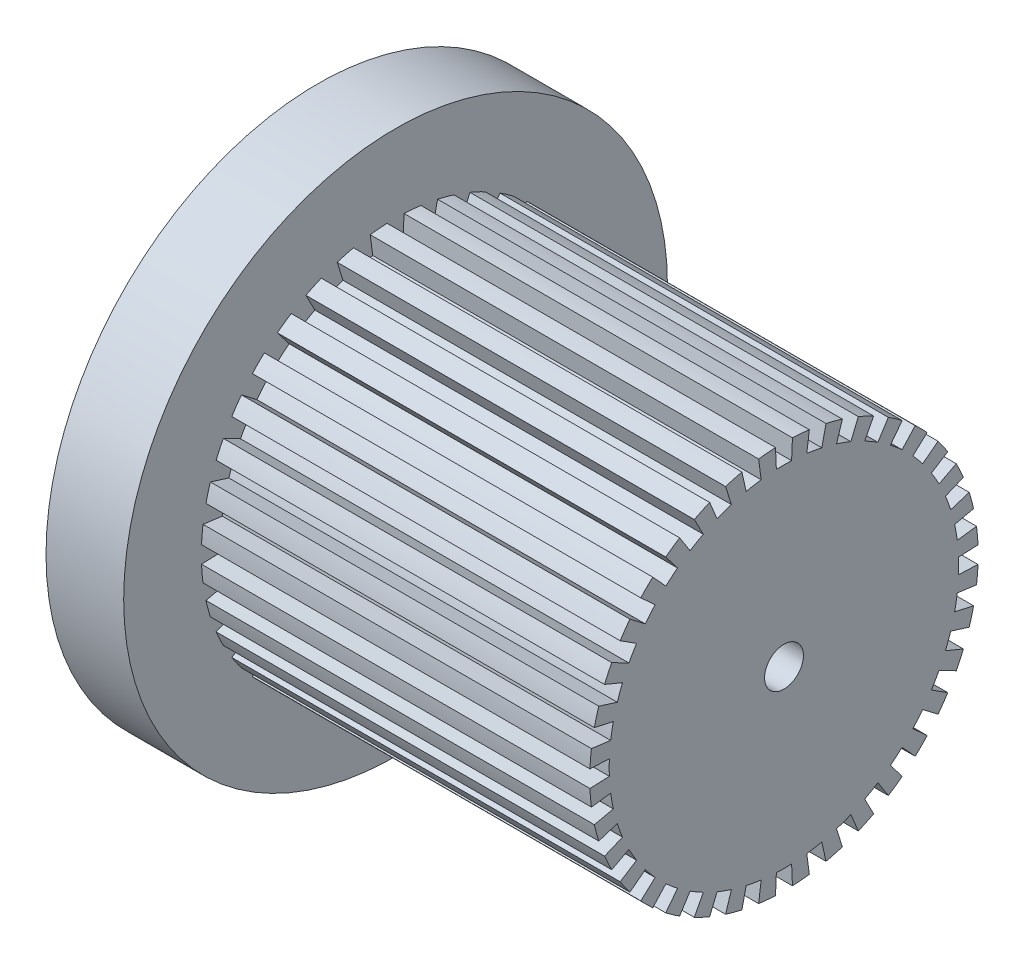
SolidWorks part; units mm, degrees
ref_plane "Front Plane" through (0, 0, 0) normal (0, 0, 1) x (1, 0, 0)
ref_plane "Top Plane" through (0, 0, 0) normal (0, 1, 0) x (1, 0, 0)
ref_plane "Right Plane" through (0, 0, 0) normal (1, 0, 0) x (0, 0, -1)
sketch "Sketch1" plane through (0, 0, 0) normal (1, 0, 0) x (0, 0, -1)
  line L0 (0, 0) -> (0, 2.2) construction
  line L1 (0.096, 2.1979) -> (0.109, 2.4976)
  line L2 (-0.096, 2.1979) -> (-0.109, 2.4976)
  line L3 (0.4762, 2.1479) -> (0.5411, 2.4407)
  line L4 (0.2872, 2.1812) -> (0.3263, 2.4786)
  line L5 (0.8419, 2.0325) -> (0.9567, 2.3097)
  line L6 (0.6616, 2.0982) -> (0.7518, 2.3843)
  line L7 (1.1821, 1.8555) -> (1.3432, 2.1085)
  line L8 (1.0158, 1.9514) -> (1.1544, 2.2175)
  line L9 (1.4863, 1.622) -> (1.689, 1.8432)
  line L10 (1.3393, 1.7454) -> (1.5219, 1.9834)
  line L11 (1.7454, 1.3393) -> (1.9834, 1.5219)
  line L12 (1.622, 1.4863) -> (1.8432, 1.689)
  line L13 (1.9514, 1.0158) -> (2.2175, 1.1544)
  line L14 (1.8555, 1.1821) -> (2.1085, 1.3432)
  line L15 (2.0982, 0.6616) -> (2.3843, 0.7518)
  line L16 (2.0325, 0.8419) -> (2.3097, 0.9567)
  line L17 (2.1812, 0.2872) -> (2.4786, 0.3263)
  line L18 (2.1479, 0.4762) -> (2.4407, 0.5411)
  line L19 (2.1979, -0.096) -> (2.4976, -0.109)
  line L20 (2.1979, 0.096) -> (2.4976, 0.109)
  line L21 (2.1479, -0.4762) -> (2.4407, -0.5411)
  line L22 (2.1812, -0.2872) -> (2.4786, -0.3263)
  line L23 (2.0325, -0.8419) -> (2.3097, -0.9567)
  line L24 (2.0982, -0.6616) -> (2.3843, -0.7518)
  line L25 (1.8555, -1.1821) -> (2.1085, -1.3432)
  line L26 (1.9514, -1.0158) -> (2.2175, -1.1544)
  line L27 (1.622, -1.4863) -> (1.8432, -1.689)
  line L28 (1.7454, -1.3393) -> (1.9834, -1.5219)
  line L29 (1.3393, -1.7454) -> (1.5219, -1.9834)
  line L30 (1.4863, -1.622) -> (1.689, -1.8432)
  line L31 (1.0158, -1.9514) -> (1.1544, -2.2175)
  line L32 (1.1821, -1.8555) -> (1.3432, -2.1085)
  line L33 (0.6616, -2.0982) -> (0.7518, -2.3843)
  line L34 (0.8419, -2.0325) -> (0.9567, -2.3097)
  line L35 (0.2872, -2.1812) -> (0.3263, -2.4786)
  line L36 (0.4762, -2.1479) -> (0.5411, -2.4407)
  line L37 (-0.096, -2.1979) -> (-0.109, -2.4976)
  line L38 (0.096, -2.1979) -> (0.109, -2.4976)
  line L39 (-0.4762, -2.1479) -> (-0.5411, -2.4407)
  line L40 (-0.2872, -2.1812) -> (-0.3263, -2.4786)
  line L41 (-0.8419, -2.0325) -> (-0.9567, -2.3097)
  line L42 (-0.6616, -2.0982) -> (-0.7518, -2.3843)
  line L43 (-1.1821, -1.8555) -> (-1.3432, -2.1085)
  line L44 (-1.0158, -1.9514) -> (-1.1544, -2.2175)
  line L45 (-1.4863, -1.622) -> (-1.689, -1.8432)
  line L46 (-1.3393, -1.7454) -> (-1.5219, -1.9834)
  line L47 (-1.7454, -1.3393) -> (-1.9834, -1.5219)
  line L48 (-1.622, -1.4863) -> (-1.8432, -1.689)
  line L49 (-1.9514, -1.0158) -> (-2.2175, -1.1544)
  line L50 (-1.8555, -1.1821) -> (-2.1085, -1.3432)
  line L51 (-2.0982, -0.6616) -> (-2.3843, -0.7518)
  line L52 (-2.0325, -0.8419) -> (-2.3097, -0.9567)
  line L53 (-2.1812, -0.2872) -> (-2.4786, -0.3263)
  line L54 (-2.1479, -0.4762) -> (-2.4407, -0.5411)
  line L55 (-2.1979, 0.096) -> (-2.4976, 0.109)
  line L56 (-2.1979, -0.096) -> (-2.4976, -0.109)
  line L57 (-2.1479, 0.4762) -> (-2.4407, 0.5411)
  line L58 (-2.1812, 0.2872) -> (-2.4786, 0.3263)
  line L59 (-2.0325, 0.8419) -> (-2.3097, 0.9567)
  line L60 (-2.0982, 0.6616) -> (-2.3843, 0.7518)
  line L61 (-1.8555, 1.1821) -> (-2.1085, 1.3432)
  line L62 (-1.9514, 1.0158) -> (-2.2175, 1.1544)
  line L63 (-1.622, 1.4863) -> (-1.8432, 1.689)
  line L64 (-1.7454, 1.3393) -> (-1.9834, 1.5219)
  line L65 (-1.3393, 1.7454) -> (-1.5219, 1.9834)
  line L66 (-1.4863, 1.622) -> (-1.689, 1.8432)
  line L67 (-1.0158, 1.9514) -> (-1.1544, 2.2175)
  line L68 (-1.1821, 1.8555) -> (-1.3432, 2.1085)
  line L69 (-0.6616, 2.0982) -> (-0.7518, 2.3843)
  line L70 (-0.8419, 2.0325) -> (-0.9567, 2.3097)
  line L71 (-0.2872, 2.1812) -> (-0.3263, 2.4786)
  line L72 (-0.4762, 2.1479) -> (-0.5411, 2.4407)
  arc A0 (0.096, 2.1979) -> (-0.096, 2.1979) centre (0, 0) ccw
  arc A1 (-0.109, 2.4976) -> (-0.3263, 2.4786) centre (0, 0) ccw
  arc A2 (0.4762, 2.1479) -> (0.2872, 2.1812) centre (0, 0) ccw
  arc A3 (0.3263, 2.4786) -> (0.109, 2.4976) centre (0, 0) ccw
  arc A4 (0.8419, 2.0325) -> (0.6616, 2.0982) centre (0, 0) ccw
  arc A5 (0.7518, 2.3843) -> (0.5411, 2.4407) centre (0, 0) ccw
  arc A6 (1.1821, 1.8555) -> (1.0158, 1.9514) centre (0, 0) ccw
  arc A7 (1.1544, 2.2175) -> (0.9567, 2.3097) centre (0, 0) ccw
  arc A8 (1.4863, 1.622) -> (1.3393, 1.7454) centre (0, 0) ccw
  arc A9 (1.5219, 1.9834) -> (1.3432, 2.1085) centre (0, 0) ccw
  arc A10 (1.7454, 1.3393) -> (1.622, 1.4863) centre (0, 0) ccw
  arc A11 (1.8432, 1.689) -> (1.689, 1.8432) centre (0, 0) ccw
  arc A12 (1.9514, 1.0158) -> (1.8555, 1.1821) centre (0, 0) ccw
  arc A13 (2.1085, 1.3432) -> (1.9834, 1.5219) centre (0, 0) ccw
  arc A14 (2.0982, 0.6616) -> (2.0325, 0.8419) centre (0, 0) ccw
  arc A15 (2.3097, 0.9567) -> (2.2175, 1.1544) centre (0, 0) ccw
  arc A16 (2.1812, 0.2872) -> (2.1479, 0.4762) centre (0, 0) ccw
  arc A17 (2.4407, 0.5411) -> (2.3843, 0.7518) centre (0, 0) ccw
  arc A18 (2.1979, -0.096) -> (2.1979, 0.096) centre (0, 0) ccw
  arc A19 (2.4976, 0.109) -> (2.4786, 0.3263) centre (0, 0) ccw
  arc A20 (2.1479, -0.4762) -> (2.1812, -0.2872) centre (0, 0) ccw
  arc A21 (2.4786, -0.3263) -> (2.4976, -0.109) centre (0, 0) ccw
  arc A22 (2.0325, -0.8419) -> (2.0982, -0.6616) centre (0, 0) ccw
  arc A23 (2.3843, -0.7518) -> (2.4407, -0.5411) centre (0, 0) ccw
  arc A24 (1.8555, -1.1821) -> (1.9514, -1.0158) centre (0, 0) ccw
  arc A25 (2.2175, -1.1544) -> (2.3097, -0.9567) centre (0, 0) ccw
  arc A26 (1.622, -1.4863) -> (1.7454, -1.3393) centre (0, 0) ccw
  arc A27 (1.9834, -1.5219) -> (2.1085, -1.3432) centre (0, 0) ccw
  arc A28 (1.3393, -1.7454) -> (1.4863, -1.622) centre (0, 0) ccw
  arc A29 (1.689, -1.8432) -> (1.8432, -1.689) centre (0, 0) ccw
  arc A30 (1.0158, -1.9514) -> (1.1821, -1.8555) centre (0, 0) ccw
  arc A31 (1.3432, -2.1085) -> (1.5219, -1.9834) centre (0, 0) ccw
  arc A32 (0.6616, -2.0982) -> (0.8419, -2.0325) centre (0, 0) ccw
  arc A33 (0.9567, -2.3097) -> (1.1544, -2.2175) centre (0, 0) ccw
  arc A34 (0.2872, -2.1812) -> (0.4762, -2.1479) centre (0, 0) ccw
  arc A35 (0.5411, -2.4407) -> (0.7518, -2.3843) centre (0, 0) ccw
  arc A36 (-0.096, -2.1979) -> (0.096, -2.1979) centre (0, 0) ccw
  arc A37 (0.109, -2.4976) -> (0.3263, -2.4786) centre (0, 0) ccw
  arc A38 (-0.4762, -2.1479) -> (-0.2872, -2.1812) centre (0, 0) ccw
  arc A39 (-0.3263, -2.4786) -> (-0.109, -2.4976) centre (0, 0) ccw
  arc A40 (-0.8419, -2.0325) -> (-0.6616, -2.0982) centre (0, 0) ccw
  arc A41 (-0.7518, -2.3843) -> (-0.5411, -2.4407) centre (0, 0) ccw
  arc A42 (-1.1821, -1.8555) -> (-1.0158, -1.9514) centre (0, 0) ccw
  arc A43 (-1.1544, -2.2175) -> (-0.9567, -2.3097) centre (0, 0) ccw
  arc A44 (-1.4863, -1.622) -> (-1.3393, -1.7454) centre (0, 0) ccw
  arc A45 (-1.5219, -1.9834) -> (-1.3432, -2.1085) centre (0, 0) ccw
  arc A46 (-1.7454, -1.3393) -> (-1.622, -1.4863) centre (0, 0) ccw
  arc A47 (-1.8432, -1.689) -> (-1.689, -1.8432) centre (0, 0) ccw
  arc A48 (-1.9514, -1.0158) -> (-1.8555, -1.1821) centre (0, 0) ccw
  arc A49 (-2.1085, -1.3432) -> (-1.9834, -1.5219) centre (0, 0) ccw
  arc A50 (-2.0982, -0.6616) -> (-2.0325, -0.8419) centre (0, 0) ccw
  arc A51 (-2.3097, -0.9567) -> (-2.2175, -1.1544) centre (0, 0) ccw
  arc A52 (-2.1812, -0.2872) -> (-2.1479, -0.4762) centre (0, 0) ccw
  arc A53 (-2.4407, -0.5411) -> (-2.3843, -0.7518) centre (0, 0) ccw
  arc A54 (-2.1979, 0.096) -> (-2.1979, -0.096) centre (0, 0) ccw
  arc A55 (-2.4976, -0.109) -> (-2.4786, -0.3263) centre (0, 0) ccw
  arc A56 (-2.1479, 0.4762) -> (-2.1812, 0.2872) centre (0, 0) ccw
  arc A57 (-2.4786, 0.3263) -> (-2.4976, 0.109) centre (0, 0) ccw
  arc A58 (-2.0325, 0.8419) -> (-2.0982, 0.6616) centre (0, 0) ccw
  arc A59 (-2.3843, 0.7518) -> (-2.4407, 0.5411) centre (0, 0) ccw
  arc A60 (-1.8555, 1.1821) -> (-1.9514, 1.0158) centre (0, 0) ccw
  arc A61 (-2.2175, 1.1544) -> (-2.3097, 0.9567) centre (0, 0) ccw
  arc A62 (-1.622, 1.4863) -> (-1.7454, 1.3393) centre (0, 0) ccw
  arc A63 (-1.9834, 1.5219) -> (-2.1085, 1.3432) centre (0, 0) ccw
  arc A64 (-1.3393, 1.7454) -> (-1.4863, 1.622) centre (0, 0) ccw
  arc A65 (-1.689, 1.8432) -> (-1.8432, 1.689) centre (0, 0) ccw
  arc A66 (-1.0158, 1.9514) -> (-1.1821, 1.8555) centre (0, 0) ccw
  arc A67 (-1.3432, 2.1085) -> (-1.5219, 1.9834) centre (0, 0) ccw
  arc A68 (-0.6616, 2.0982) -> (-0.8419, 2.0325) centre (0, 0) ccw
  arc A69 (-0.9567, 2.3097) -> (-1.1544, 2.2175) centre (0, 0) ccw
  arc A70 (-0.2872, 2.1812) -> (-0.4762, 2.1479) centre (0, 0) ccw
  arc A71 (-0.5411, 2.4407) -> (-0.7518, 2.3843) centre (0, 0) ccw
  point P146 (0, 0)
extrude "Boss-Extrude1" add sketch "Sketch1" along normal blind 1
sketch "Sketch2" plane through (1, 0, 0) normal (1, 0, 0) x (0, 0, -1)
  circle A0 centre (0, 0) radius 7
extrude "Boss-Extrude2" add sketch "Sketch2" along normal blind 2
sketch "Sketch3" plane through (3, 0, 0) normal (1, 0, 0) x (0, 0, -1)
  line L0 (0, 0) -> (0, 4.5) construction
  line L1 (0.1963, 4.4957) -> (0.2181, 4.9952)
  line L2 (-0.1963, 4.4957) -> (-0.2181, 4.9952)
  line L3 (0.974, 4.3933) -> (1.0822, 4.8815)
  line L4 (0.5874, 4.4615) -> (0.6526, 4.9572)
  line L5 (1.7221, 4.1575) -> (1.9134, 4.6194)
  line L6 (1.3532, 4.2917) -> (1.5035, 4.7686)
  line L7 (2.4178, 3.7953) -> (2.6865, 4.217)
  line L8 (2.0779, 3.9915) -> (2.3087, 4.4351)
  line L9 (3.0402, 3.3177) -> (3.378, 3.6864)
  line L10 (2.7394, 3.5701) -> (3.0438, 3.9668)
  line L11 (3.5701, 2.7394) -> (3.9668, 3.0438)
  line L12 (3.3177, 3.0402) -> (3.6864, 3.378)
  line L13 (3.9915, 2.0779) -> (4.4351, 2.3087)
  line L14 (3.7953, 2.4178) -> (4.217, 2.6865)
  line L15 (4.2917, 1.3532) -> (4.7686, 1.5035)
  line L16 (4.1575, 1.7221) -> (4.6194, 1.9134)
  line L17 (4.4615, 0.5874) -> (4.9572, 0.6526)
  line L18 (4.3933, 0.974) -> (4.8815, 1.0822)
  line L19 (4.4957, -0.1963) -> (4.9952, -0.2181)
  line L20 (4.4957, 0.1963) -> (4.9952, 0.2181)
  line L21 (4.3933, -0.974) -> (4.8815, -1.0822)
  line L22 (4.4615, -0.5874) -> (4.9572, -0.6526)
  line L23 (4.1575, -1.7221) -> (4.6194, -1.9134)
  line L24 (4.2917, -1.3532) -> (4.7686, -1.5035)
  line L25 (3.7953, -2.4178) -> (4.217, -2.6865)
  line L26 (3.9915, -2.0779) -> (4.4351, -2.3087)
  line L27 (3.3177, -3.0402) -> (3.6864, -3.378)
  line L28 (3.5701, -2.7394) -> (3.9668, -3.0438)
  line L29 (2.7394, -3.5701) -> (3.0438, -3.9668)
  line L30 (3.0402, -3.3177) -> (3.378, -3.6864)
  line L31 (2.0779, -3.9915) -> (2.3087, -4.4351)
  line L32 (2.4178, -3.7953) -> (2.6865, -4.217)
  line L33 (1.3532, -4.2917) -> (1.5035, -4.7686)
  line L34 (1.7221, -4.1575) -> (1.9134, -4.6194)
  line L35 (0.5874, -4.4615) -> (0.6526, -4.9572)
  line L36 (0.974, -4.3933) -> (1.0822, -4.8815)
  line L37 (-0.1963, -4.4957) -> (-0.2181, -4.9952)
  line L38 (0.1963, -4.4957) -> (0.2181, -4.9952)
  line L39 (-0.974, -4.3933) -> (-1.0822, -4.8815)
  line L40 (-0.5874, -4.4615) -> (-0.6526, -4.9572)
  line L41 (-1.7221, -4.1575) -> (-1.9134, -4.6194)
  line L42 (-1.3532, -4.2917) -> (-1.5035, -4.7686)
  line L43 (-2.4178, -3.7953) -> (-2.6865, -4.217)
  line L44 (-2.0779, -3.9915) -> (-2.3087, -4.4351)
  line L45 (-3.0402, -3.3177) -> (-3.378, -3.6864)
  line L46 (-2.7394, -3.5701) -> (-3.0438, -3.9668)
  line L47 (-3.5701, -2.7394) -> (-3.9668, -3.0438)
  line L48 (-3.3177, -3.0402) -> (-3.6864, -3.378)
  line L49 (-3.9915, -2.0779) -> (-4.4351, -2.3087)
  line L50 (-3.7953, -2.4178) -> (-4.217, -2.6865)
  line L51 (-4.2917, -1.3532) -> (-4.7686, -1.5035)
  line L52 (-4.1575, -1.7221) -> (-4.6194, -1.9134)
  line L53 (-4.4615, -0.5874) -> (-4.9572, -0.6526)
  line L54 (-4.3933, -0.974) -> (-4.8815, -1.0822)
  line L55 (-4.4957, 0.1963) -> (-4.9952, 0.2181)
  line L56 (-4.4957, -0.1963) -> (-4.9952, -0.2181)
  line L57 (-4.3933, 0.974) -> (-4.8815, 1.0822)
  line L58 (-4.4615, 0.5874) -> (-4.9572, 0.6526)
  line L59 (-4.1575, 1.7221) -> (-4.6194, 1.9134)
  line L60 (-4.2917, 1.3532) -> (-4.7686, 1.5035)
  line L61 (-3.7953, 2.4178) -> (-4.217, 2.6865)
  line L62 (-3.9915, 2.0779) -> (-4.4351, 2.3087)
  line L63 (-3.3177, 3.0402) -> (-3.6864, 3.378)
  line L64 (-3.5701, 2.7394) -> (-3.9668, 3.0438)
  line L65 (-2.7394, 3.5701) -> (-3.0438, 3.9668)
  line L66 (-3.0402, 3.3177) -> (-3.378, 3.6864)
  line L67 (-2.0779, 3.9915) -> (-2.3087, 4.4351)
  line L68 (-2.4178, 3.7953) -> (-2.6865, 4.217)
  line L69 (-1.3532, 4.2917) -> (-1.5035, 4.7686)
  line L70 (-1.7221, 4.1575) -> (-1.9134, 4.6194)
  line L71 (-0.5874, 4.4615) -> (-0.6526, 4.9572)
  line L72 (-0.974, 4.3933) -> (-1.0822, 4.8815)
  arc A0 (0.1963, 4.4957) -> (-0.1963, 4.4957) centre (0, 0) ccw
  arc A1 (-0.2181, 4.9952) -> (-0.6526, 4.9572) centre (0, 0) ccw
  arc A2 (0.974, 4.3933) -> (0.5874, 4.4615) centre (0, 0) ccw
  arc A3 (0.6526, 4.9572) -> (0.2181, 4.9952) centre (0, 0) ccw
  arc A4 (1.7221, 4.1575) -> (1.3532, 4.2917) centre (0, 0) ccw
  arc A5 (1.5035, 4.7686) -> (1.0822, 4.8815) centre (0, 0) ccw
  arc A6 (2.4178, 3.7953) -> (2.0779, 3.9915) centre (0, 0) ccw
  arc A7 (2.3087, 4.4351) -> (1.9134, 4.6194) centre (0, 0) ccw
  arc A8 (3.0402, 3.3177) -> (2.7394, 3.5701) centre (0, 0) ccw
  arc A9 (3.0438, 3.9668) -> (2.6865, 4.217) centre (0, 0) ccw
  arc A10 (3.5701, 2.7394) -> (3.3177, 3.0402) centre (0, 0) ccw
  arc A11 (3.6864, 3.378) -> (3.378, 3.6864) centre (0, 0) ccw
  arc A12 (3.9915, 2.0779) -> (3.7953, 2.4178) centre (0, 0) ccw
  arc A13 (4.217, 2.6865) -> (3.9668, 3.0438) centre (0, 0) ccw
  arc A14 (4.2917, 1.3532) -> (4.1575, 1.7221) centre (0, 0) ccw
  arc A15 (4.6194, 1.9134) -> (4.4351, 2.3087) centre (0, 0) ccw
  arc A16 (4.4615, 0.5874) -> (4.3933, 0.974) centre (0, 0) ccw
  arc A17 (4.8815, 1.0822) -> (4.7686, 1.5035) centre (0, 0) ccw
  arc A18 (4.4957, -0.1963) -> (4.4957, 0.1963) centre (0, 0) ccw
  arc A19 (4.9952, 0.2181) -> (4.9572, 0.6526) centre (0, 0) ccw
  arc A20 (4.3933, -0.974) -> (4.4615, -0.5874) centre (0, 0) ccw
  arc A21 (4.9572, -0.6526) -> (4.9952, -0.2181) centre (0, 0) ccw
  arc A22 (4.1575, -1.7221) -> (4.2917, -1.3532) centre (0, 0) ccw
  arc A23 (4.7686, -1.5035) -> (4.8815, -1.0822) centre (0, 0) ccw
  arc A24 (3.7953, -2.4178) -> (3.9915, -2.0779) centre (0, 0) ccw
  arc A25 (4.4351, -2.3087) -> (4.6194, -1.9134) centre (0, 0) ccw
  arc A26 (3.3177, -3.0402) -> (3.5701, -2.7394) centre (0, 0) ccw
  arc A27 (3.9668, -3.0438) -> (4.217, -2.6865) centre (0, 0) ccw
  arc A28 (2.7394, -3.5701) -> (3.0402, -3.3177) centre (0, 0) ccw
  arc A29 (3.378, -3.6864) -> (3.6864, -3.378) centre (0, 0) ccw
  arc A30 (2.0779, -3.9915) -> (2.4178, -3.7953) centre (0, 0) ccw
  arc A31 (2.6865, -4.217) -> (3.0438, -3.9668) centre (0, 0) ccw
  arc A32 (1.3532, -4.2917) -> (1.7221, -4.1575) centre (0, 0) ccw
  arc A33 (1.9134, -4.6194) -> (2.3087, -4.4351) centre (0, 0) ccw
  arc A34 (0.5874, -4.4615) -> (0.974, -4.3933) centre (0, 0) ccw
  arc A35 (1.0822, -4.8815) -> (1.5035, -4.7686) centre (0, 0) ccw
  arc A36 (-0.1963, -4.4957) -> (0.1963, -4.4957) centre (0, 0) ccw
  arc A37 (0.2181, -4.9952) -> (0.6526, -4.9572) centre (0, 0) ccw
  arc A38 (-0.974, -4.3933) -> (-0.5874, -4.4615) centre (0, 0) ccw
  arc A39 (-0.6526, -4.9572) -> (-0.2181, -4.9952) centre (0, 0) ccw
  arc A40 (-1.7221, -4.1575) -> (-1.3532, -4.2917) centre (0, 0) ccw
  arc A41 (-1.5035, -4.7686) -> (-1.0822, -4.8815) centre (0, 0) ccw
  arc A42 (-2.4178, -3.7953) -> (-2.0779, -3.9915) centre (0, 0) ccw
  arc A43 (-2.3087, -4.4351) -> (-1.9134, -4.6194) centre (0, 0) ccw
  arc A44 (-3.0402, -3.3177) -> (-2.7394, -3.5701) centre (0, 0) ccw
  arc A45 (-3.0438, -3.9668) -> (-2.6865, -4.217) centre (0, 0) ccw
  arc A46 (-3.5701, -2.7394) -> (-3.3177, -3.0402) centre (0, 0) ccw
  arc A47 (-3.6864, -3.378) -> (-3.378, -3.6864) centre (0, 0) ccw
  arc A48 (-3.9915, -2.0779) -> (-3.7953, -2.4178) centre (0, 0) ccw
  arc A49 (-4.217, -2.6865) -> (-3.9668, -3.0438) centre (0, 0) ccw
  arc A50 (-4.2917, -1.3532) -> (-4.1575, -1.7221) centre (0, 0) ccw
  arc A51 (-4.6194, -1.9134) -> (-4.4351, -2.3087) centre (0, 0) ccw
  arc A52 (-4.4615, -0.5874) -> (-4.3933, -0.974) centre (0, 0) ccw
  arc A53 (-4.8815, -1.0822) -> (-4.7686, -1.5035) centre (0, 0) ccw
  arc A54 (-4.4957, 0.1963) -> (-4.4957, -0.1963) centre (0, 0) ccw
  arc A55 (-4.9952, -0.2181) -> (-4.9572, -0.6526) centre (0, 0) ccw
  arc A56 (-4.3933, 0.974) -> (-4.4615, 0.5874) centre (0, 0) ccw
  arc A57 (-4.9572, 0.6526) -> (-4.9952, 0.2181) centre (0, 0) ccw
  arc A58 (-4.1575, 1.7221) -> (-4.2917, 1.3532) centre (0, 0) ccw
  arc A59 (-4.7686, 1.5035) -> (-4.8815, 1.0822) centre (0, 0) ccw
  arc A60 (-3.7953, 2.4178) -> (-3.9915, 2.0779) centre (0, 0) ccw
  arc A61 (-4.4351, 2.3087) -> (-4.6194, 1.9134) centre (0, 0) ccw
  arc A62 (-3.3177, 3.0402) -> (-3.5701, 2.7394) centre (0, 0) ccw
  arc A63 (-3.9668, 3.0438) -> (-4.217, 2.6865) centre (0, 0) ccw
  arc A64 (-2.7394, 3.5701) -> (-3.0402, 3.3177) centre (0, 0) ccw
  arc A65 (-3.378, 3.6864) -> (-3.6864, 3.378) centre (0, 0) ccw
  arc A66 (-2.0779, 3.9915) -> (-2.4178, 3.7953) centre (0, 0) ccw
  arc A67 (-2.6865, 4.217) -> (-3.0438, 3.9668) centre (0, 0) ccw
  arc A68 (-1.3532, 4.2917) -> (-1.7221, 4.1575) centre (0, 0) ccw
  arc A69 (-1.9134, 4.6194) -> (-2.3087, 4.4351) centre (0, 0) ccw
  arc A70 (-0.5874, 4.4615) -> (-0.974, 4.3933) centre (0, 0) ccw
  arc A71 (-1.0822, 4.8815) -> (-1.5035, 4.7686) centre (0, 0) ccw
  point P186 (0, 0)
  dimension "D1" = 36
extrude "Boss-Extrude3" add sketch "Sketch3" along normal blind 10
sketch "Sketch4" plane through (13, 0, 0) normal (1, 0, 0) x (0, 0, -1)
  circle A0 centre (0, 0) radius 0.5
extrude "Cut-Extrude1" cut sketch "Sketch4" against normal through all
